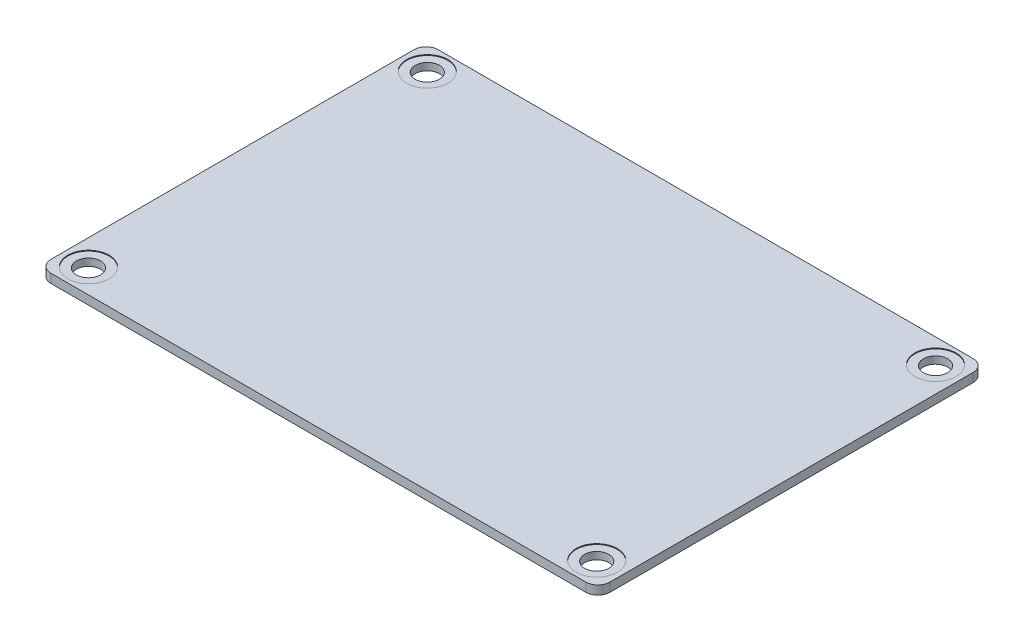
SolidWorks part; units mm, degrees
ref_plane "Спереди" through (0, 0, 0) normal (0, 0, 1) x (1, 0, 0)
ref_plane "Сверху" through (0, 0, 0) normal (0, 1, 0) x (1, 0, 0)
ref_plane "Справа" through (0, 0, 0) normal (1, 0, 0) x (0, 0, -1)
sketch "Эскиз1" plane through (0, 0, 0) normal (0, 1, 0) x (1, 0, 0)
  line L1 (33.15, -24) -> (-33.15, -24)
  line L2 (34.65, -22.5) -> (34.65, 22.5)
  line L3 (33.15, 24) -> (-33.15, 24)
  line L4 (-34.65, -22.5) -> (-34.65, 22.5)
  line L5 (34.65, -24) -> (-34.65, 24) construction
  line L6 (34.65, 24) -> (-34.65, -24) construction
  line L7 (-31.5, -21) -> (31.5, -21) construction
  line L8 (-31.5, -21) -> (-31.5, 21) construction
  line L9 (-31.5, 21) -> (31.5, 21) construction
  line L10 (31.5, -21) -> (31.5, 21) construction
  line L11 (-31.5, -21) -> (31.5, 21) construction
  line L12 (-31.5, 21) -> (31.5, -21) construction
  circle A0 centre (-31.5, 21) radius 2.55
  circle A1 centre (31.5, 21) radius 2.55
  circle A2 centre (31.5, -21) radius 2.55
  circle A3 centre (-31.5, -21) radius 2.55
  arc A4 (-33.15, -24) -> (-34.65, -22.5) centre (-33.15, -22.5) cw
  arc A5 (33.15, -24) -> (34.65, -22.5) centre (33.15, -22.5) ccw
  arc A6 (34.65, 22.5) -> (33.15, 24) centre (33.15, 22.5) ccw
  arc A7 (-33.15, 24) -> (-34.65, 22.5) centre (-33.15, 22.5) ccw
  point P0 (0, 0)
  point P6 (0, 0)
  dimension "D3" = 5.1
  dimension "D6" = 1.5
  dimension "D1" = 69.3
  dimension "D2" = 48
  dimension "D4" = 63
  dimension "D5" = 42
extrude "Бобышка-Вытянуть1" add sketch "Эскиз1" along normal blind 1.1
ref_plane "Плоскость1" through (0, 0.1, 0) normal (0, -1, 0) x (-1, 0, 0)
sketch "Эскиз2" plane through (0, 0.1, 0) normal (0, -1, 0) x (-1, 0, 0)
  circle A0 centre (31.5, -21) radius 2.55 construction
  circle A1 centre (-31.5, -21) radius 2.55 construction
  circle A2 centre (-31.5, 21) radius 2.55 construction
  circle A3 centre (31.5, 21) radius 2.55 construction
  circle A4 centre (31.5, -21) radius 2.55
  circle A5 centre (-31.5, -21) radius 2.55
  circle A6 centre (-31.5, 21) radius 2.55
  circle A7 centre (31.5, 21) radius 2.55
  circle A8 centre (31.5, 21) radius 1.5
  circle A9 centre (-31.5, 21) radius 1.5
  circle A10 centre (-31.5, -21) radius 1.5
  circle A11 centre (31.5, -21) radius 1.5
  dimension "D1" = 3
extrude "Бобышка-Вытянуть2" add sketch "Эскиз2" against normal offset from surface (0.9 mm away) 0.1 up to face at (0, 1.1, 0)
